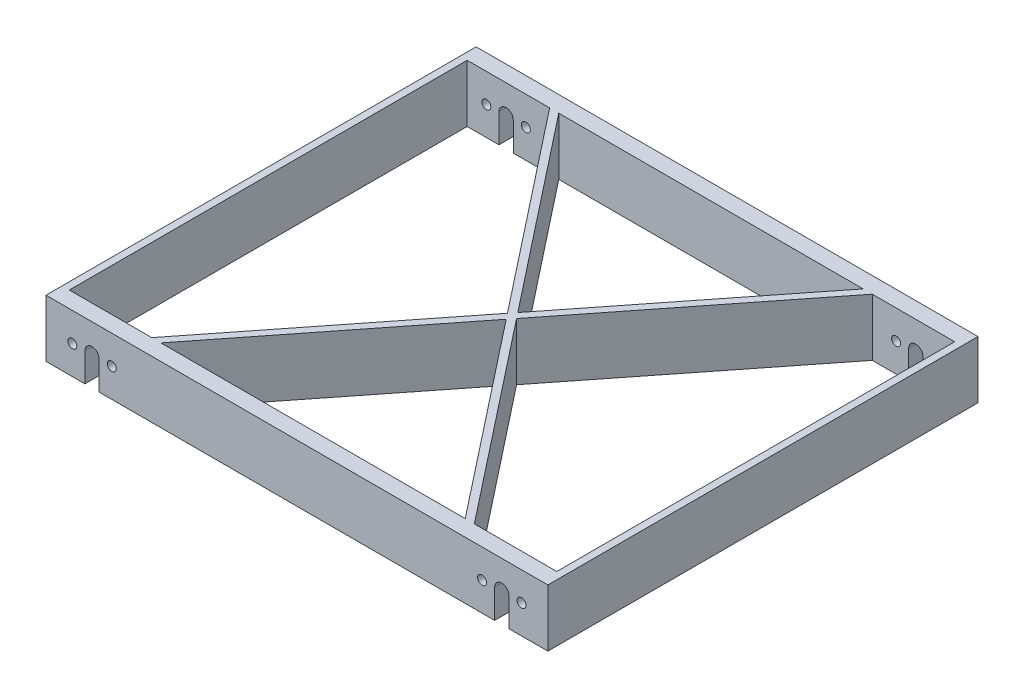
SolidWorks part; units mm, degrees
ref_plane "Front Plane" through (0, 0, 0) normal (0, 0, 1) x (1, 0, 0)
ref_plane "Top Plane" through (0, 0, 0) normal (0, 1, 0) x (1, 0, 0)
ref_plane "Right Plane" through (0, 0, 0) normal (1, 0, 0) x (0, 0, -1)
sketch "Sketch1" plane through (0, 0, 0) normal (0, 1, 0) x (1, 0, 0)
  line L0 (-57.15, 60) -> (-57.15, -60) construction
  line L1 (-70, -60) -> (70, -60)
  line L2 (-70, -60) -> (-70, 60)
  line L3 (-70, 60) -> (70, 60)
  line L4 (70, -60) -> (70, 60)
  line L5 (-70, -60) -> (70, 60) construction
  line L6 (-70, 60) -> (70, -60) construction
  line L7 (-68, -55.5) -> (68, -55.5)
  line L8 (-68, -55.5) -> (-68, 55.5)
  line L9 (-68, 55.5) -> (68, 55.5)
  line L10 (68, -55.5) -> (68, 55.5)
  line L11 (-68, -55.5) -> (68, 55.5) construction
  line L12 (-68, 55.5) -> (68, -55.5) construction
  line L13 (57.15, 60) -> (57.15, -60) construction
  line L14 (0, 0) -> (-57.15, 0) construction
  line L15 (0, 0) -> (57.15, 0) construction
  line L16 (-45, 55.5) -> (-1.2731, 0)
  line L17 (-1.2731, 0) -> (-45, -55.5)
  line L18 (-42.4538, -55.5) -> (0, -1.6159)
  line L19 (0, -1.6159) -> (42.4538, -55.5)
  line L20 (45, -55.5) -> (1.2731, 0)
  line L21 (1.2731, 0) -> (45, 55.5)
  line L22 (42.4538, 55.5) -> (0, 1.6159)
  line L23 (0, 1.6159) -> (-42.4538, 55.5)
  point P0 (0, 0)
  point P6 (0, 0)
  point P29 (5.4565, -1.4512)
  point P31 (4.4116, 7.9526)
  point P32 (-1.2771, 13.4091)
  point P33 (0, 0)
  point P34 (0, 0)
  point P35 (0, 0)
  point P36 (45.2774, 55.5)
  point P37 (1.9872, 2.1044)
  point P38 (0, -2.3215)
  point P39 (0, 0)
  dimension "D1" = 120
  dimension "D2" = 140
  dimension "D3" = 2
  dimension "D4" = 4.5
  dimension "D5" = 114.3
  dimension "D6" = 2
  dimension "D7" = 2
  dimension "D8" = 2
  dimension "D9" = 90
extrude "Boss-Extrude1" add sketch "Sketch1" along normal blind 16 contours L1 L4 L3 L2 L10 L7 L8 L9 | L22 L23 L9 L16 L17 L7 L18 L19 L20 L21
sketch "Sketch2" plane through (0, 0, 60) normal (0, 0, 1) x (1, 0, 0)
  line L0 (-59.15, 8) -> (-59.15, 0)
  line L1 (-70, 0) -> (70, 0) construction
  line L2 (-55.15, 8) -> (-55.15, 0)
  line L3 (-57.15, 0) -> (-57.15, 16) construction
  line L4 (-70, 16) -> (70, 16) construction
  line L5 (0, 0) -> (0, 16) construction
  line L6 (-62.65, 8) -> (-51.65, 8) construction
  line L7 (55.15, 8) -> (55.15, 0)
  line L8 (59.15, 8) -> (59.15, 0)
  arc A0 (-59.15, 8) -> (-55.15, 8) centre (-57.15, 8) cw
  circle A1 centre (-62.65, 8) radius 1.25
  circle A2 centre (-51.65, 8) radius 1.25
  arc A3 (59.15, 8) -> (55.15, 8) centre (57.15, 8) ccw
  circle A4 centre (51.65, 8) radius 1.25
  circle A5 centre (62.65, 8) radius 1.25
  point P18 (0, 0)
  line M7 (-70, 0) -> (70, 0)
  dimension "D3" = 2.5
  dimension "D1" = 4
  dimension "D2" = 11
  dimension "D4" = 114.3
extrude "Cut-Extrude1" cut sketch "Sketch2" against normal through all contours A0 L0 L2 M7 | A2 | A1 | L8 A3 L7 M7 | A4 | A5
equation "\"D7@Sketch1\"=\"D6@Sketch1\""
equation "\"D8@Sketch1\"=\"D6@Sketch1\""
